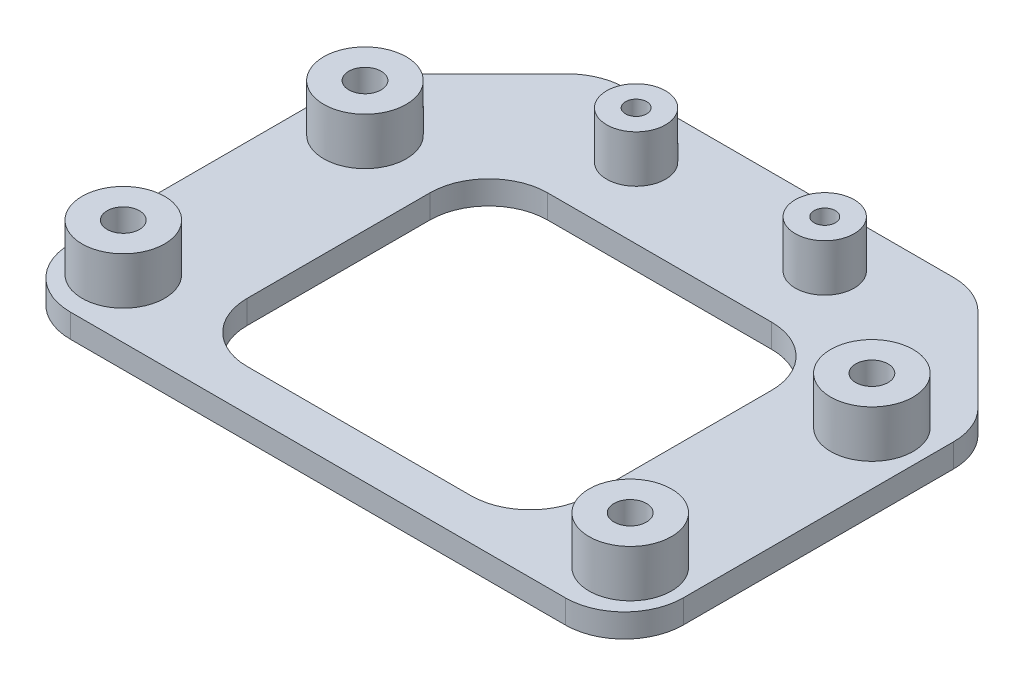
SolidWorks part; units mm, degrees
ref_plane "Front Plane" through (0, 0, 0) normal (0, 0, 1) x (1, 0, 0)
ref_plane "Top Plane" through (0, 0, 0) normal (0, 1, 0) x (1, 0, 0)
ref_plane "Right Plane" through (0, 0, 0) normal (1, 0, 0) x (0, 0, -1)
sketch "Sketch1" plane through (0, 0, 0) normal (0, 1, 0) x (1, 0, 0)
  line L1 (-26, -20) -> (26, -20)
  line L2 (-26, -20) -> (-26, 20)
  line L3 (-26, 20) -> (26, 20)
  line L4 (26, -20) -> (26, 20)
  line L5 (-26, -20) -> (26, 20) construction
  line L6 (-26, 20) -> (26, -20) construction
  point P0 (0, 0)
  dimension "D1" = 52
  dimension "D2" = 40
extrude "Boss-Extrude1" add sketch "Sketch1" along normal blind 2
sketch "Sketch2" plane through (0, 2, 0) normal (0, 1, 0) x (1, 0, 0)
  line L0 (0, 0) -> (0, -50000) construction
  line L1 (-26, -20) -> (26, -20) construction
  line L2 (-21.5, -15) -> (21.5, -15) construction
  line L3 (-21.5, -15) -> (-21.5, 5.5) construction
  line L4 (-21.5, 5.5) -> (21.5, 5.5) construction
  line L5 (21.5, -15) -> (21.5, 5.5) construction
  line L6 (-21.5, -15) -> (21.5, 5.5) construction
  line L7 (-21.5, 5.5) -> (21.5, -15) construction
  line L8 (-8, 15) -> (8, 15) construction
  line L9 (26, 20) -> (-26, 20) construction
  circle A0 centre (8, 15) radius 0.9
  circle A1 centre (-8, 15) radius 0.9
  circle A2 centre (-21.5, 5.5) radius 1.375
  circle A3 centre (-21.5, -15) radius 1.375
  circle A4 centre (21.5, -15) radius 1.375
  circle A5 centre (21.5, 5.5) radius 1.375
  point P3 (0, -4.75)
  point P13 (0, 15)
  dimension "D6" = 1.8
  dimension "D7" = 2.75
  dimension "D1" = 43
  dimension "D2" = 20.5
  dimension "D3" = 5
  dimension "D4" = 16
  dimension "D5" = 5
extrude "Cut-Extrude1" cut sketch "Sketch2" against normal through all
sketch "Sketch3" plane through (0, 2, 0) normal (0, 1, 0) x (1, 0, 0)
  circle A0 centre (-21.5, 5.5) radius 3.5
  circle A1 centre (-21.5, -15) radius 3.5
  circle A2 centre (21.5, -15) radius 3.5
  circle A3 centre (21.5, 5.5) radius 3.5
  circle A4 centre (8, 15) radius 2.5
  circle A5 centre (-8, 15) radius 2.5
  circle A6 centre (-8, 15) radius 0.9 construction
  circle A7 centre (8, 15) radius 0.9 construction
  circle A8 centre (21.5, 5.5) radius 1.375 construction
  circle A9 centre (21.5, -15) radius 1.375 construction
  circle A10 centre (-21.5, -15) radius 1.375 construction
  circle A11 centre (-21.5, 5.5) radius 1.375 construction
  circle A12 centre (-21.5, 5.5) radius 1.375
  circle A13 centre (-21.5, -15) radius 1.375
  circle A14 centre (21.5, -15) radius 1.375
  circle A15 centre (21.5, 5.5) radius 1.375
  circle A16 centre (8, 15) radius 0.9
  circle A17 centre (-8, 15) radius 0.9
  dimension "D1" = 7
  dimension "D2" = 5
extrude "Boss-Extrude2" add sketch "Sketch3" along normal blind 4
sketch "Sketch4" plane through (0, 2, 0) normal (0, 1, 0) x (1, 0, 0)
  line L0 (0, 0) -> (0, 50000) construction
  line L1 (8, 12.5) -> (8, 9) construction
  line L2 (-14.5, -16.5) -> (14.5, -16.5)
  line L3 (-14.5, -16.5) -> (-14.5, 9)
  line L4 (-14.5, 9) -> (14.5, 9)
  line L5 (14.5, -16.5) -> (14.5, 9)
  line L6 (-14.5, -16.5) -> (14.5, 9) construction
  line L7 (-14.5, 9) -> (14.5, -16.5) construction
  line L8 (18, -15) -> (14.5, -15) construction
  line L9 (8, -16.5) -> (8, -20) construction
  line L10 (-26, -20) -> (26, -20) construction
  circle A0 centre (8, 15) radius 2.5 construction
  circle A1 centre (21.5, -15) radius 3.5 construction
  circle A2 centre (8, 15) radius 2.5 construction
  point P2 (0, -3.75)
  point P21 (0, 0)
  point P22 (0, 0)
  point P23 (14.5588, -15)
  point P24 (7.8771, 12.503)
  point P26 (8, 12.5)
  dimension "D1" = 3.5
extrude "Cut-Extrude2" cut sketch "Sketch4" against normal through all
chamfer "Chamfer1" distance 10 angle 45 2 edges at (26, 1, -20) (-26, 1, -20)
fillet "Fillet1" radius 5 10 edges at (-14.5, 1, 16.5) (14.5, 1, 16.5) (14.5, 1, -9) (-14.5, 1, -9) (-26, 1, -10) (-26, 1, 20) (26, 1, 20) (26, 1, -10) (16, 1, -20) (-16, 1, -20)
